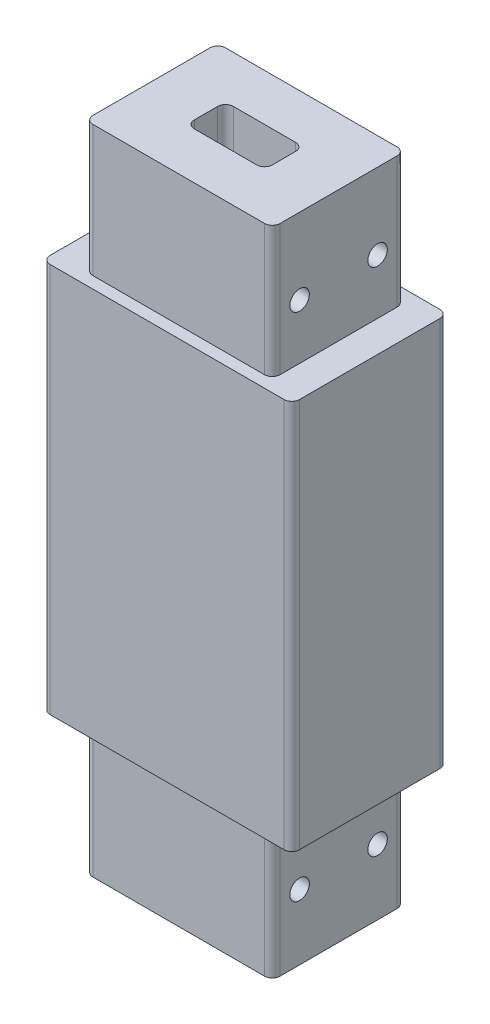
SolidWorks part; units mm, degrees
material "EVA"
ref_plane "Front Plane" through (0, 0, 0) normal (0, 0, 1) x (1, 0, 0)
ref_plane "Top Plane" through (0, 0, 0) normal (0, 1, 0) x (1, 0, 0)
ref_plane "Right Plane" through (0, 0, 0) normal (1, 0, 0) x (0, 0, -1)
sketch "Sketch1" plane through (0, 0, 0) normal (0, 1, 0) x (1, 0, 0)
  line L1 (-16, -10) -> (16, -10)
  line L2 (-16, -10) -> (-16, 10)
  line L3 (-16, 10) -> (16, 10)
  line L4 (16, -10) -> (16, 10)
  line L5 (-16, -10) -> (16, 10) construction
  line L6 (-16, 10) -> (16, -10) construction
  point P0 (0, 0)
  dimension "D1" = 32
extrude "Boss-Extrude1" add sketch "Sketch1" along normal blind 50
ref_plane "Plane1" through (0, 25, 0) normal (0, -1, 0) x (-1, 0, 0)
sketch "Sketch2" plane through (0, 25, 0) normal (0, 1, 0) x (1, 0, 0)
  line L1 (-11, -8.5) -> (11, -8.5)
  line L2 (-12, -7.5) -> (-12, 7.5)
  line L3 (-11, 8.5) -> (11, 8.5)
  line L4 (12, -7.5) -> (12, 7.5)
  line L5 (-12, -8.5) -> (12, 8.5) construction
  line L6 (-12, 8.5) -> (12, -8.5) construction
  arc A0 (11, -8.5) -> (12, -7.5) centre (11, -7.5) ccw
  arc A1 (-11, -8.5) -> (-12, -7.5) centre (-11, -7.5) cw
  arc A2 (-12, 7.5) -> (-11, 8.5) centre (-11, 7.5) cw
  arc A3 (11, 8.5) -> (12, 7.5) centre (11, 7.5) cw
  point P0 (0, 0)
  dimension "D3" = 1
  dimension "D1" = 22
  dimension "D2" = 15
extrude "Boss-Extrude2" add sketch "Sketch2" along normal mid plane 83.6
sketch "Sketch3" plane through (0, 66.8, 0) normal (0, 1, 0) x (1, 0, 0)
  line L1 (-4, -2.5) -> (4, -2.5)
  line L2 (-5, -1.5) -> (-5, 1.5)
  line L3 (-4, 2.5) -> (4, 2.5)
  line L4 (5, -1.5) -> (5, 1.5)
  line L5 (-5, -2.5) -> (5, 2.5) construction
  line L6 (-5, 2.5) -> (5, -2.5) construction
  arc A0 (4, -2.5) -> (5, -1.5) centre (4, -1.5) ccw
  arc A1 (-4, -2.5) -> (-5, -1.5) centre (-4, -1.5) cw
  arc A2 (-5, 1.5) -> (-4, 2.5) centre (-4, 1.5) cw
  arc A3 (4, 2.5) -> (5, 1.5) centre (4, 1.5) cw
  point P0 (0, 0)
  dimension "D3" = 1
  dimension "D1" = 5
  dimension "D2" = 10
extrude "Cut-Extrude1" cut sketch "Sketch3" against normal up to surface (16.8 mm away) up to face at (0, 50, 0)
sketch "Sketch4" plane through (0, -16.8, 0) normal (0, -1, 0) x (1, 0, 0)
  line L1 (-4, -2.5) -> (4, -2.5)
  line L2 (-5, -1.5) -> (-5, 1.5)
  line L3 (-4, 2.5) -> (4, 2.5)
  line L4 (5, -1.5) -> (5, 1.5)
  line L5 (-5, -2.5) -> (5, 2.5) construction
  line L6 (-5, 2.5) -> (5, -2.5) construction
  arc A0 (-4, -2.5) -> (-5, -1.5) centre (-4, -1.5) cw
  arc A1 (4, -2.5) -> (5, -1.5) centre (4, -1.5) ccw
  arc A2 (4, 2.5) -> (5, 1.5) centre (4, 1.5) cw
  arc A3 (-5, 1.5) -> (-4, 2.5) centre (-4, 1.5) cw
  point P0 (0, 0)
  dimension "D3" = 1
  dimension "D1" = 5
  dimension "D2" = 10
extrude "Cut-Extrude2" cut sketch "Sketch4" against normal up to surface (16.8 mm away) up to face at (0, 0, 0)
sketch "Sketch5" plane through (0, 50, 0) normal (0, 1, 0) x (1, 0, 0)
  circle A0 centre (0, 0) radius 0.5
  dimension "D1" = 1
extrude "Cut-Extrude3" cut sketch "Sketch5" against normal through all
hole_wizard "M2.5x0.45 Tapped Hole1" positions "Sketch7" profile "Sketch8" tap size "M2.5x0.45" standard "ANSI Metric" end condition through all
sketch "Sketch7" plane through (-12, 0, 0) normal (-1, 0, 0) x (0, 0, 1)
  line L1 (-7.5, 0) -> (7.5, 0) construction
  line L6 (10, 50) -> (10, 0) construction
  point P0 (5, -8.4)
  dimension "D1" = 8.4
  dimension "D2" = 5
sketch "Sketch8" plane through (-12, -8.4, 5) normal (0, 1, 0) x (0, 0, 1)
  line L0 (0, 0) -> (0, 28)
  line L1 (0, 28) -> (1.25, 28)
  line L2 (1.25, 28) -> (1.25, 0)
  line L5 (1.25, 0) -> (0, 0)
  line L11 (0, -6.35) -> (0, 107.95) construction
  dimension "Thread Major Dia." = 2.5
  dimension "Thru Tap Drill Depth" = 28
hole_wizard "M2.5x0.45 Tapped Hole2" positions "Sketch11" profile "Sketch12" tap size "M2.5x0.45" standard "ANSI Metric" end condition through all
sketch "Sketch11" plane through (12, 0, 0) normal (1, 0, 0) x (0, 0, -1)
  line L0 (-7.5, 0) -> (7.5, 0) construction
  line L3 (10, 50) -> (10, 0) construction
  point P0 (5, -8.4)
  dimension "D1" = 8.4
  dimension "D2" = 5
sketch "Sketch12" plane through (12, -8.4, -5) normal (0, 1, 0) x (0, 0, -1)
  line L0 (0, 0) -> (0, 28)
  line L1 (0, 28) -> (1.25, 28)
  line L2 (1.25, 28) -> (1.25, 0)
  line L5 (1.25, 0) -> (0, 0)
  line L11 (0, -6.35) -> (0, 107.95) construction
  dimension "Thread Major Dia." = 2.5
  dimension "Thru Tap Drill Depth" = 28
fillet "Fillet1" radius 1 4 edges at (-16, 25, 10) (16, 25, 10) (16, 25, -10) (-16, 25, -10)
hole_wizard "M2.5x0.45 Tapped Hole4" positions "Sketch14" profile "Sketch15" tap size "M2.5x0.45" standard "ANSI Metric" end condition through all
sketch "Sketch14" plane through (-12, 0, 0) normal (-1, 0, 0) x (0, 0, 1)
  line L0 (-7.5, 50) -> (7.5, 50) construction
  line L4 (-10, 0) -> (-10, 50) construction
  line L5 (10, 50) -> (10, 0) construction
  point P0 (-5, 57.05)
  point P2 (5, 57.05)
  dimension "D2" = 5
  dimension "D1" = 7.05
  dimension "D3" = 5
sketch "Sketch15" plane through (-12, 57.05, -5) normal (0, 1, 0) x (0, 0, 1)
  line L0 (0, 0) -> (0, 28)
  line L1 (0, 28) -> (1.25, 28)
  line L2 (1.25, 28) -> (1.25, 0)
  line L5 (1.25, 0) -> (0, 0)
  line L11 (0, -6.35) -> (0, 107.95) construction
  dimension "Thread Major Dia." = 2.5
  dimension "Thru Tap Drill Depth" = 28
equation "\"D2@Sketch1\" = \"t_total\""
equation "\"D2@Sketch2\" = \"t_total\" - 0.005m"
equation "\"D2@Sketch7\" = \"t_total\" / 4"
equation "\"D2@Sketch11\" = \"t_total\" / 4"
equation "\"D2@Sketch14\" = \"t_total\" / 4"
equation "\"D3@Sketch14\" = \"t_total\" / 4"
equation "\"t_total\"= 0.0200m"
